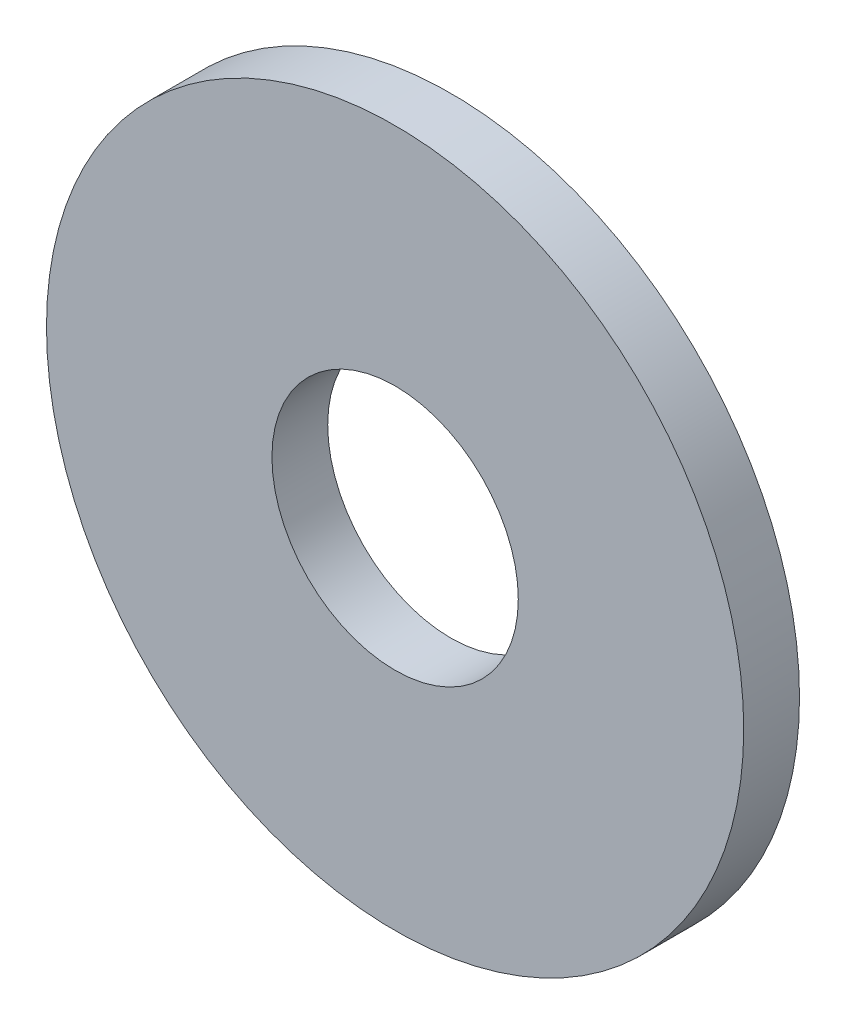
SolidWorks part; units mm, degrees
material "Plain Carbon Steel"
ref_plane "Front Plane" through (0, 0, 0) normal (0, 0, 1) x (1, 0, 0)
ref_plane "Top Plane" through (0, 0, 0) normal (0, 1, 0) x (1, 0, 0)
ref_plane "Right Plane" through (0, 0, 0) normal (1, 0, 0) x (0, 0, -1)
sketch "Sketch1" plane through (0, 0, 0) normal (0, 0, 1) x (1, 0, 0)
  circle A0 centre (0, 0) radius 7.5
  circle A1 centre (0, 0) radius 2.65
  dimension "D1" = 5.3
  dimension "D2" = 15
extrude "Boss-Extrude1" add sketch "Sketch1" along normal blind 1.2
